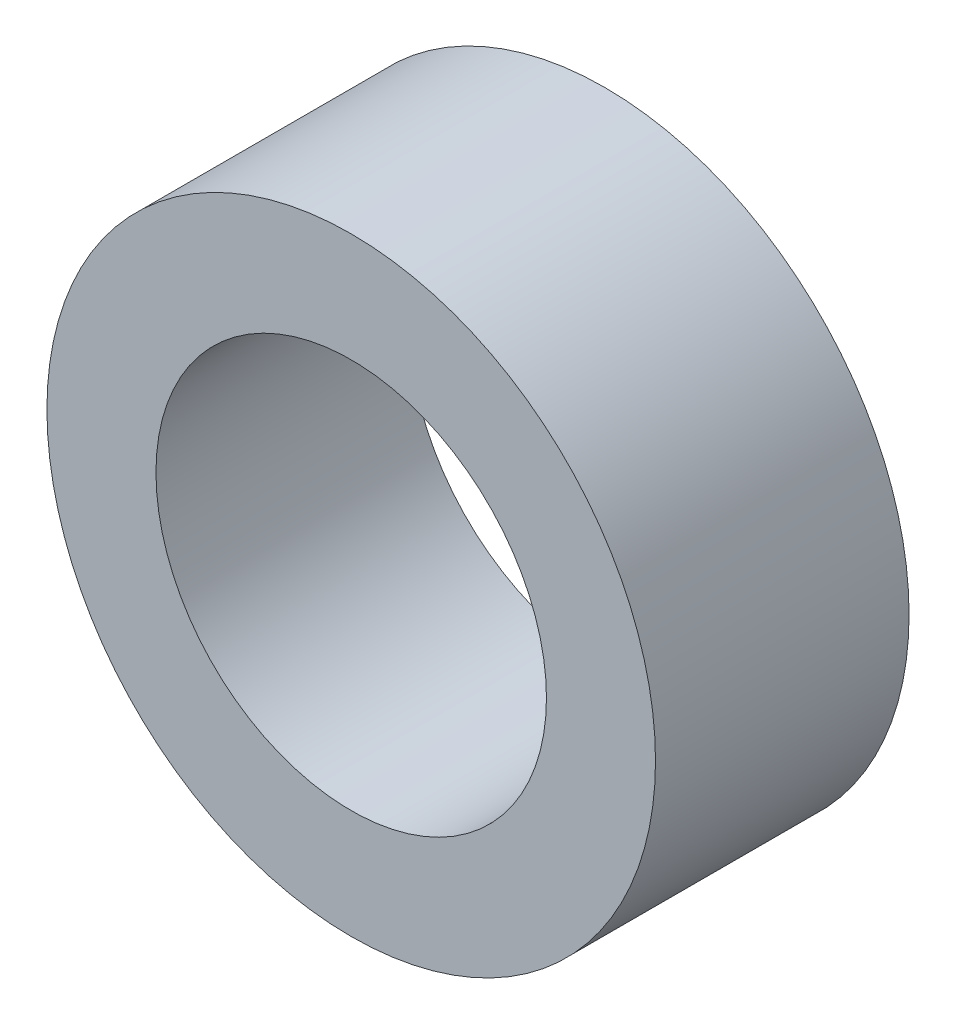
SolidWorks part; units mm, degrees
ref_plane "Front Plane" through (0, 0, 0) normal (0, 0, 1) x (1, 0, 0)
ref_plane "Top Plane" through (0, 0, 0) normal (0, 1, 0) x (1, 0, 0)
ref_plane "Right Plane" through (0, 0, 0) normal (1, 0, 0) x (0, 0, -1)
sketch "Sketch1" plane through (0, 0, 0) normal (0, 0, 1) x (1, 0, 0)
  circle A0 centre (0, 0) radius 6
  circle A1 centre (0, 0) radius 3.85
  dimension "D1" = 7.7
  dimension "D2" = 12
extrude "Boss-Extrude1" add sketch "Sketch1" along normal blind 5
